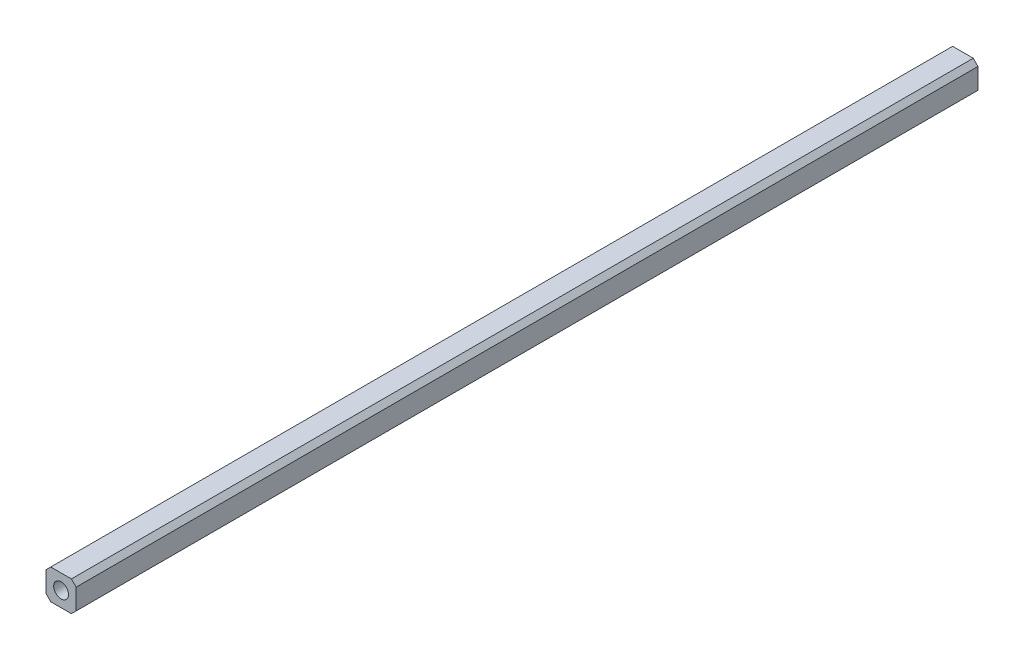
SolidWorks part; units mm, degrees
material "1060 Alloy"
ref_plane "Front Plane" through (0, 0, 0) normal (0, 0, 1) x (1, 0, 0)
ref_plane "Top Plane" through (0, 0, 0) normal (0, 1, 0) x (1, 0, 0)
ref_plane "Right Plane" through (0, 0, 0) normal (1, 0, 0) x (0, 0, -1)
sketch "Sketch1" plane through (0, 0, 0) normal (0, 0, 1) x (1, 0, 0)
  line L1 (-6.35, 6.35) -> (6.35, 6.35)
  line L2 (-6.35, 6.35) -> (-6.35, -6.35)
  line L3 (-6.35, -6.35) -> (6.35, -6.35)
  line L4 (6.35, 6.35) -> (6.35, -6.35)
  line L5 (-6.35, 6.35) -> (6.35, -6.35) construction
  line L6 (-6.35, -6.35) -> (6.35, 6.35) construction
  point P0 (0, 0)
  dimension "D1" = 12.7
  dimension "D2" = 12.7
extrude "Boss-Extrude1" add sketch "Sketch1" along normal mid plane 380 contours L2 L3 L4 L1
sketch "Sketch2" plane through (0, 0, 190) normal (0, 0, 1) x (1, 0, 0)
  circle A0 centre (0, 0) radius 3.125
  dimension "D1" = 6.25
extrude "Cut-Extrude1" cut sketch "Sketch2" against normal blind 10
chamfer "Chamfer1" distance 2 angle 45 4 edges at (-6.35, 6.35, 0) (-6.35, -6.35, 0) (6.35, -6.35, 0) (6.35, 6.35, 0)
